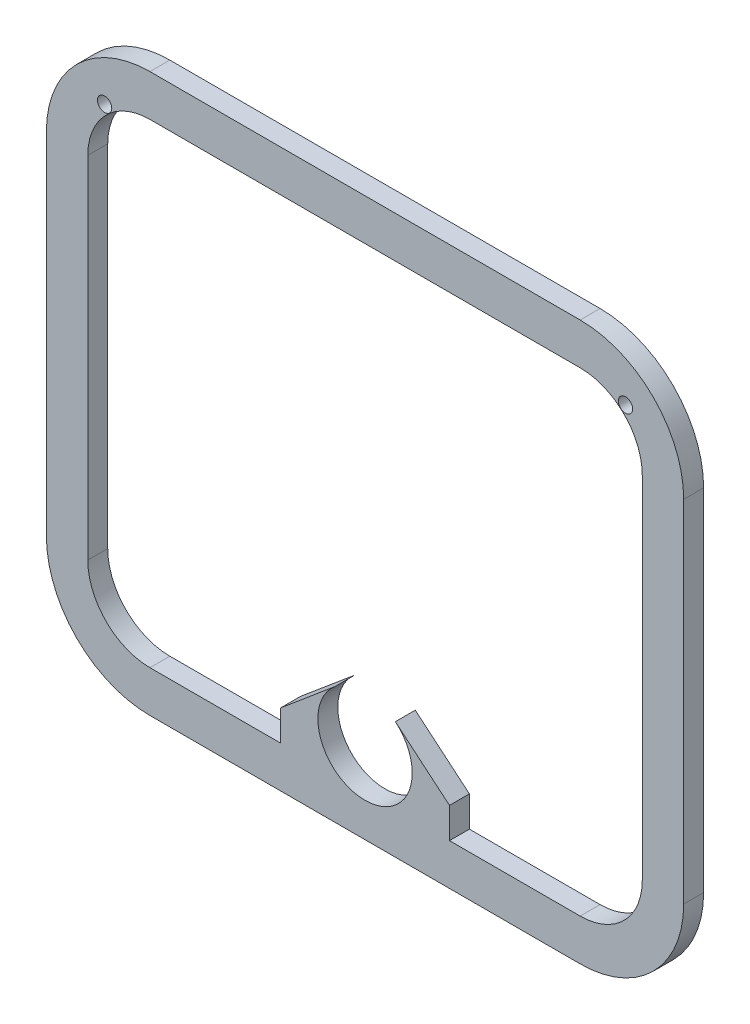
SolidWorks part; units mm, degrees
material "Delrin"
ref_plane "Front Plane" through (0, 0, 0) normal (0, 0, 1) x (1, 0, 0)
ref_plane "Top Plane" through (0, 0, 0) normal (0, 1, 0) x (1, 0, 0)
ref_plane "Right Plane" through (0, 0, 0) normal (1, 0, 0) x (0, 0, -1)
sketch "Sketch1" plane through (0, 0, 0) normal (0, 0, 1) x (1, 0, 0)
  line L0 (-17.145, -18.923) -> (-9.6321, -18.923)
  line L1 (17.145, 22.225) -> (-17.145, 22.225)
  line L2 (25.4, 13.97) -> (25.4, -13.97)
  line L3 (17.145, -22.225) -> (-17.145, -22.225)
  line L4 (-25.4, 13.97) -> (-25.4, -13.97)
  line L5 (25.4, 22.225) -> (-25.4, -22.225) construction
  line L6 (25.4, -22.225) -> (-25.4, 22.225) construction
  line L7 (9.6321, -18.923) -> (17.145, -18.923)
  line L10 (-22.098, 13.97) -> (-22.098, -13.97)
  line L13 (22.098, 13.97) -> (22.098, -13.97)
  line L14 (17.145, 18.923) -> (-17.145, 18.923)
  line L18 (0, 18.415) -> (0, -18.415) construction
  line L21 (2.4164, -12.8683) -> (9.6321, -18.923)
  line L22 (-2.4164, -12.8683) -> (-9.6321, -18.923)
  line L36 (17.145, -18.923) -> (-17.145, -18.923) construction
  arc A0 (-2.4164, -12.8683) -> (2.4164, -12.8683) centre (0, -15.748) ccw
  arc A1 (-17.145, 22.225) -> (-25.4, 13.97) centre (-17.145, 13.97) ccw
  arc A2 (17.145, 22.225) -> (25.4, 13.97) centre (17.145, 13.97) cw
  arc A3 (25.4, -13.97) -> (17.145, -22.225) centre (17.145, -13.97) cw
  arc A4 (-17.145, -22.225) -> (-25.4, -13.97) centre (-17.145, -13.97) cw
  arc A5 (-17.145, -18.923) -> (-22.098, -13.97) centre (-17.145, -13.97) cw
  arc A6 (22.098, -13.97) -> (17.145, -18.923) centre (17.145, -13.97) cw
  arc A7 (17.145, 18.923) -> (22.098, 13.97) centre (17.145, 13.97) cw
  arc A8 (-17.145, 18.923) -> (-22.098, 13.97) centre (-17.145, 13.97) ccw
  circle A9 centre (-20.7596, 18.1647) radius 0.5715
  circle A10 centre (20.7596, 18.1647) radius 0.5715
  point P0 (0, 0)
  dimension "D4" = 7.5184
  dimension "D6" = 8.255
  dimension "D7" = 8.255
  dimension "D8" = 8.255
  dimension "D9" = 8.255
  dimension "D5" = 1.143
  dimension "D1" = 50.8
  dimension "D2" = 44.45
  dimension "D10" = 3.302
  dimension "D3" = 3.175
  dimension "D11" = 5.5372
extrude "Boss-Extrude1" add sketch "Sketch1" along normal blind 1.5875
sketch "Sketch2" plane through (0, 0, 1.5875) normal (0, 0, 1) x (1, 0, 0)
  line L0 (-9.6321, -18.923) -> (-2.4164, -12.8683) construction
  line L1 (-9.6321, -18.923) -> (-6.731, -18.923)
  line L2 (-9.6321, -18.923) -> (-9.6321, -16.4887)
  line L3 (-9.6321, -16.4887) -> (-6.731, -16.4887)
  line L4 (-6.731, -18.923) -> (-6.731, -16.4887)
  line L5 (0, -1000) -> (0, 49000) construction
  line L6 (9.6321, -18.923) -> (9.6321, -16.4887)
  line L7 (9.6321, -16.4887) -> (6.731, -16.4887)
  line L8 (6.731, -18.923) -> (6.731, -16.4887)
  line L9 (9.6321, -18.923) -> (6.731, -18.923)
  arc A0 (-2.4164, -12.8683) -> (2.4164, -12.8683) centre (0, -15.748) ccw construction
  dimension "D1" = 6.731
extrude "Cut-Extrude1" cut sketch "Sketch2" against normal up to next
